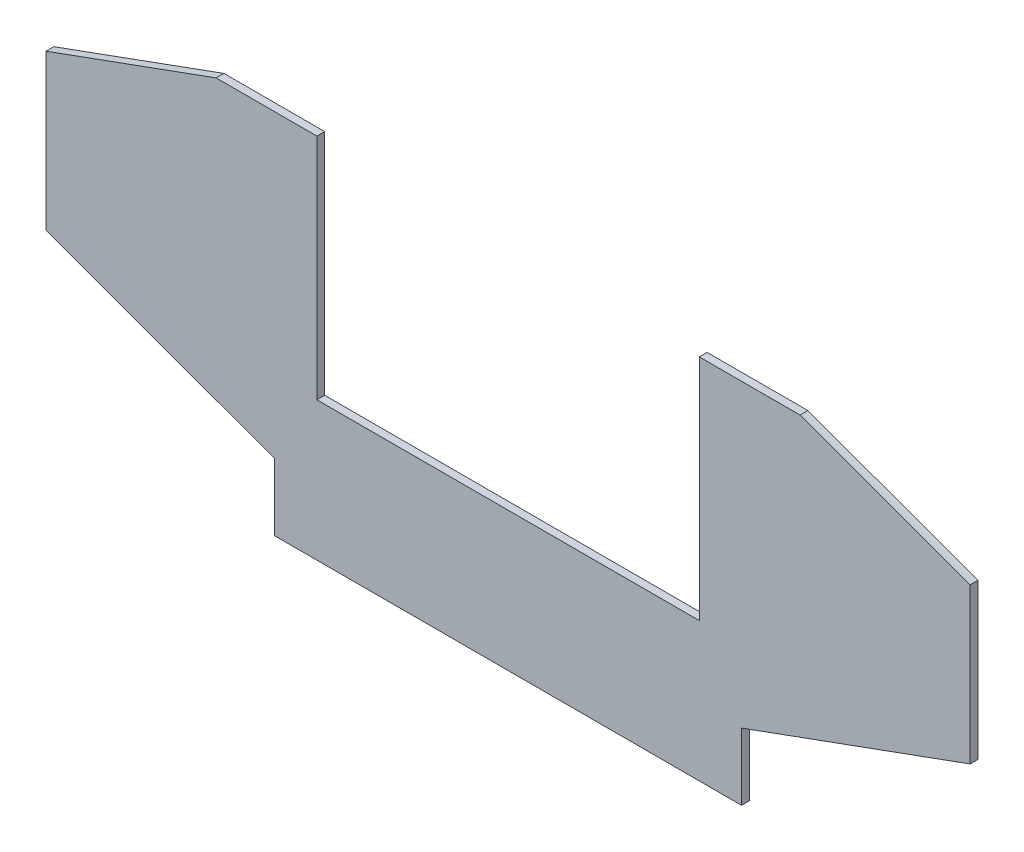
SolidWorks part; units mm, degrees
material "Plastique personnalisé"
ref_plane "Plan de face" through (0, 0, 0) normal (0, 0, 1) x (1, 0, 0)
ref_plane "Plan de dessus" through (0, 0, 0) normal (0, 1, 0) x (1, 0, 0)
ref_plane "Plan de droite" through (0, 0, 0) normal (1, 0, 0) x (0, 0, -1)
sketch "Esquisse1" plane through (0, 0, 0) normal (0, 0, 1) x (1, 0, 0)
  line L0 (59.8246, -58.3616) -> (-59.8246, -58.3616)
  line L2 (150, 0) -> (74.8246, 0) construction
  line L4 (74.8246, 35.7572) -> (49, 35.7572)
  line L6 (59.8246, -41.2167) -> (-59.8246, -41.2167) construction
  line L7 (0, -18.7684) -> (0, -62.3616) construction
  line L8 (49, -22.7684) -> (49, 35.7572)
  line L10 (74.8246, 35.7572) -> (118.4222, 19.889)
  line L11 (118.4222, 19.889) -> (118.4222, -19.889)
  line L12 (118.4222, -19.889) -> (59.8246, -41.2167)
  line L14 (59.8246, -41.2167) -> (59.8246, -58.3616)
  line L22 (74.8246, -62.3616) -> (74.8246, 62.3616) construction
  line L23 (-49, -22.7684) -> (-49, 35.7572)
  line L24 (-74.8246, 35.7572) -> (-49, 35.7572)
  line L25 (-74.8246, 35.7572) -> (-118.4222, 19.889)
  line L26 (-118.4222, 19.889) -> (-118.4222, -19.889)
  line L27 (-118.4222, -19.889) -> (-59.8246, -41.2167)
  line L28 (-59.8246, -41.2167) -> (-59.8246, -58.3616)
  line L29 (49, -22.7684) -> (-49, -22.7684)
  point P25 (0, 0)
extrude "Boss.-Extru.1" add sketch "Esquisse1" along normal blind 2 contours L8 L4 L10 L11 L12 L14 L0 L28 L27 L26 L25 L24 L23 L29
